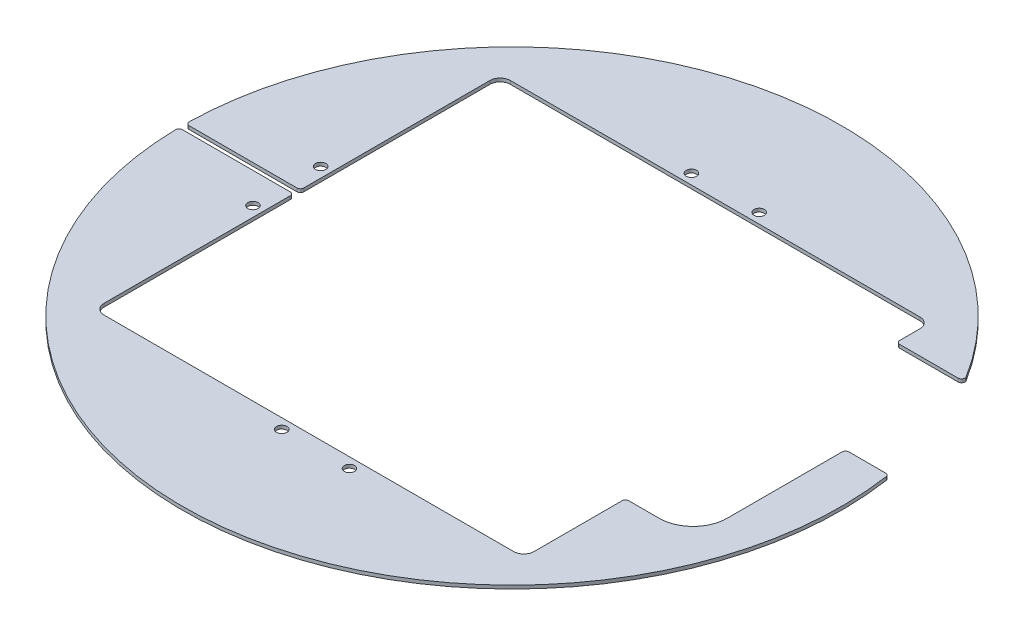
SolidWorks part; units mm, degrees
material "Thornel Mat VMA"
ref_plane "前视基准面" through (0, 0, 0) normal (0, 0, 1) x (1, 0, 0)
ref_plane "上视基准面" through (0, 0, 0) normal (0, 1, 0) x (1, 0, 0)
ref_plane "右视基准面" through (0, 0, 0) normal (1, 0, 0) x (0, 0, -1)
other "Configuration Table"
sketch "草图1" plane through (0, 0, 0) normal (0, 1, 0) x (1, 0, 0)
  line L1 (-63.5, 60) -> (63.5, 60)
  line L2 (-63.5, 60) -> (-63.5, -60)
  line L3 (-63.5, -60) -> (63.5, -60)
  line L4 (63.5, 60) -> (63.5, -60)
  line L5 (-63.5, 60) -> (63.5, -60) construction
  line L6 (-63.5, -60) -> (63.5, 60) construction
  circle A0 centre (0, 0) radius 97.3627
  circle A1 centre (0, 0) radius 87.3627 construction
  point P0 (0, 0)
  dimension "D3" = 10
  dimension "D1" = 120
  dimension "D2" = 127
extrude "凸台-拉伸1" add sketch "草图1" along normal mid plane 1
sketch "草图2" plane through (0, 0.5, 0) normal (0, 1, 0) x (1, 0, 0)
  line L0 (92.6256, -30) -> (63.5, -30)
  line L1 (63.5, -60) -> (63.5, 60) construction
  line L2 (63.5, 50) -> (83.5434, 50)
  line L3 (63.5, 50) -> (63.5, -30)
  circle A0 centre (0, 0) radius 97.3627 construction
  arc A1 (92.6256, -30) -> (83.5434, 50) centre (0, 0) ccw
  dimension "D1" = 30
  dimension "D2" = 50
extrude "切除-拉伸1" cut sketch "草图2" against normal mid plane 32
sketch "草图3" plane through (0, 0.5, 0) normal (0, 1, 0) x (1, 0, 0)
  line L0 (-63.5, 60) -> (-63.5, -60) construction
  line L1 (-103.5, -1) -> (-23.5, -1)
  line L2 (-103.5, -1) -> (-103.5, 1)
  line L3 (-103.5, 1) -> (-23.5, 1)
  line L4 (-23.5, -1) -> (-23.5, 1)
  line L5 (-103.5, -1) -> (-23.5, 1) construction
  line L6 (-103.5, 1) -> (-23.5, -1) construction
  point P0 (-63.5, 0)
  dimension "D1" = 2
  dimension "D2" = 80
extrude "切除-拉伸2" cut sketch "草图3" against normal mid plane 22
sketch "草图4" plane through (0, 0.5, 0) normal (0, 1, 0) x (1, 0, 0)
  line L0 (83.5, -30) -> (83.5, 15)
  line L1 (63.5, -30) -> (92.6256, -30) construction
  line L2 (83.5, 15) -> (96.2003, 15)
  line L3 (83.5, -30) -> (92.6256, -30)
  line L4 (63.5, -60) -> (63.5, -30) construction
  arc A0 (92.6256, -30) -> (96.2003, 15) centre (0, 0) ccw
  arc A1 (-97.3576, -1) -> (92.6256, -30) centre (0, 0) ccw construction
  dimension "D1" = 20
  dimension "D2" = 45
extrude "凸台-拉伸2" add sketch "草图4" against normal up to surface (1 mm away) up to face at (-2.843, -0.5, 43.7913)
fillet "圆角1" radius 3 2 edges at (63.5, 0, 60) (-63.5, 0, 60)
fillet "圆角2" radius 3 2 edges at (63.5, 0, -60) (-63.5, 0, -60)
fillet "圆角3" radius 10 1 edges at (83.5, 0, 30)
sketch "草图5" plane through (0, 0.5, 0) normal (0, 1, 0) x (1, 0, 0)
  circle A0 centre (-66.5, -10) radius 1.25 construction
  circle A1 centre (-66.5, 10) radius 1.25 construction
  circle A2 centre (15, -63) radius 1.25 construction
  circle A3 centre (-5, -63) radius 1.25 construction
  circle A4 centre (-66.5, -10) radius 1.25 construction
  circle A5 centre (-66.5, 10) radius 1.25 construction
  circle A6 centre (15, -63) radius 1.25 construction
  circle A7 centre (-5, -63) radius 1.25 construction
  circle A8 centre (10, 63) radius 1.25 construction
  circle A9 centre (-10, 63) radius 1.25 construction
  circle A10 centre (10, 63) radius 1.25 construction
  circle A11 centre (-10, 63) radius 1.25 construction
  circle A12 centre (-66.5, 10) radius 1.525
  circle A13 centre (-66.5, -10) radius 1.525
  circle A14 centre (-10, 63) radius 1.525
  circle A15 centre (10, 63) radius 1.525
  circle A16 centre (-5, -63) radius 1.525
  circle A17 centre (15, -63) radius 1.525
  dimension "D1" = 3.05
extrude "切除-拉伸3" cut sketch "草图5" against normal up to surface (1 mm away) up to face at (-4.0453, -0.5, -50.7149)
fillet "圆角4" radius 1 5 edges at (63.5, 0, 30) (-63.5, 0, 1) (-97.3576, 0, 1) (96.2003, 0, -15) (83.5, 0, -15)
fillet "圆角5" radius 1 4 edges at (-97.3576, 0, -1) (-63.5, 0, -1) (63.5, 0, -50) (83.5434, 0, -50)
